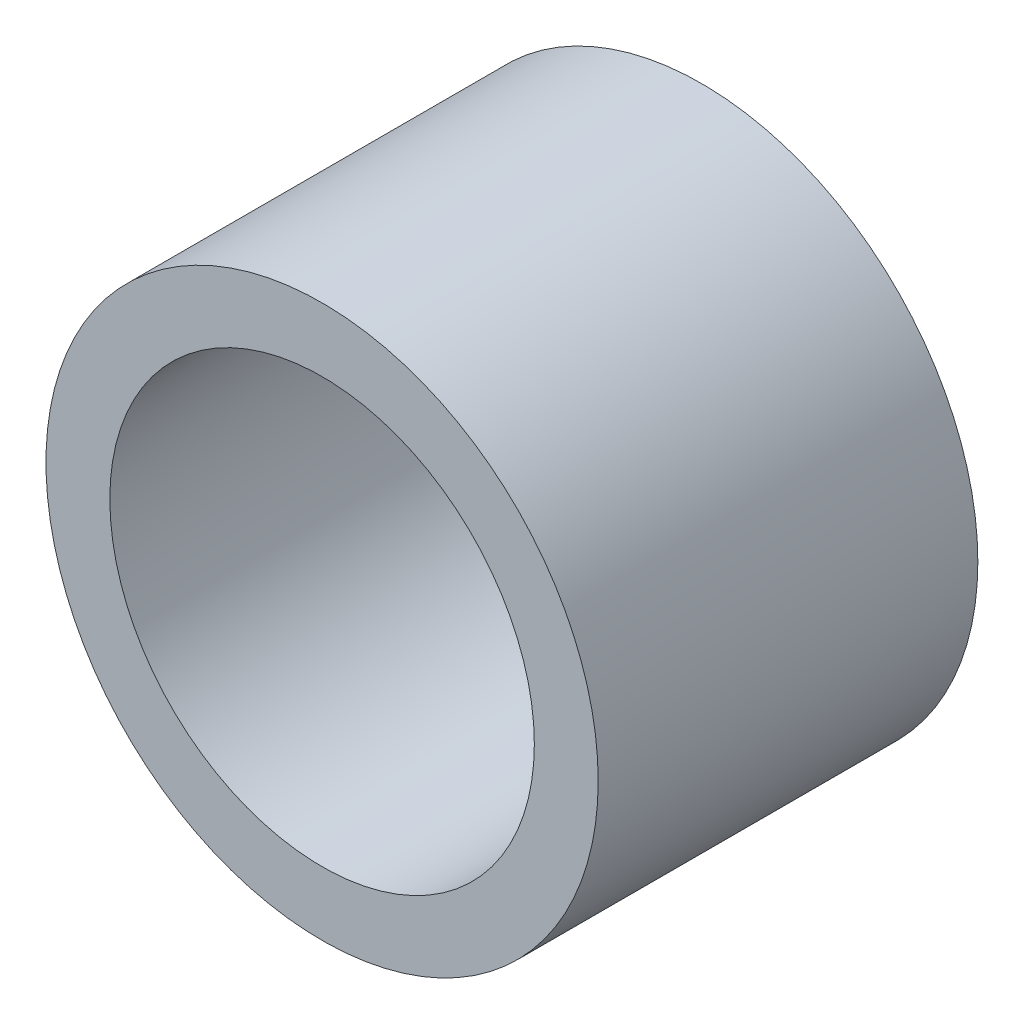
SolidWorks part; units mm, degrees
ref_plane "Front Plane" through (0, 0, 0) normal (0, 0, 1) x (1, 0, 0)
ref_plane "Top Plane" through (0, 0, 0) normal (0, 1, 0) x (1, 0, 0)
ref_plane "Right Plane" through (0, 0, 0) normal (1, 0, 0) x (0, 0, -1)
sketch "S01 - Hardened sixteen millimetre running surface" plane through (0, 0, 0) normal (0, 0, 1) x (1, 0, 0)
  circle A0 centre (0, 0) radius 8
  circle A1 centre (0, 0) radius 6.15
  dimension "D1" = 12.3
  dimension "D2" = 16
extrude "01 - Hardened sixteen millimetre running surface" add sketch "S01 - Hardened sixteen millimetre running surface" along normal blind 11
